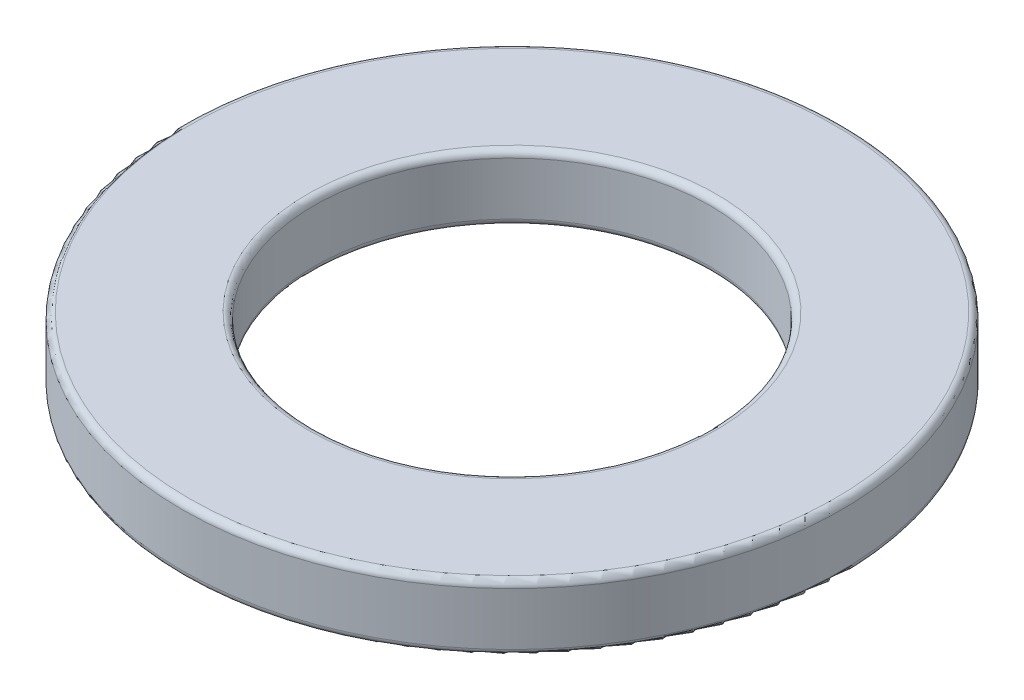
SolidWorks part; units mm, degrees
ref_plane "Front Plane" through (0, 0, 0) normal (0, 0, 1) x (1, 0, 0)
ref_plane "Top Plane" through (0, 0, 0) normal (0, 1, 0) x (1, 0, 0)
ref_plane "Right Plane" through (0, 0, 0) normal (1, 0, 0) x (0, 0, -1)
sketch "Sketch1" plane through (0, 0, 0) normal (0, 1, 0) x (1, 0, 0)
  circle A0 centre (0, 0) radius 7.62
  circle A1 centre (0, 0) radius 12.7
  dimension "D1" = 15.24
  dimension "D2" = 5.08
extrude "Boss-Extrude1" add sketch "Sketch1" along normal blind 2.54
fillet "Fillet1" radius 0.254 4 edges at (0, 0, 7.62) (0, 0, 12.7) (0, 2.54, 7.62) (0, 2.54, 12.7)
